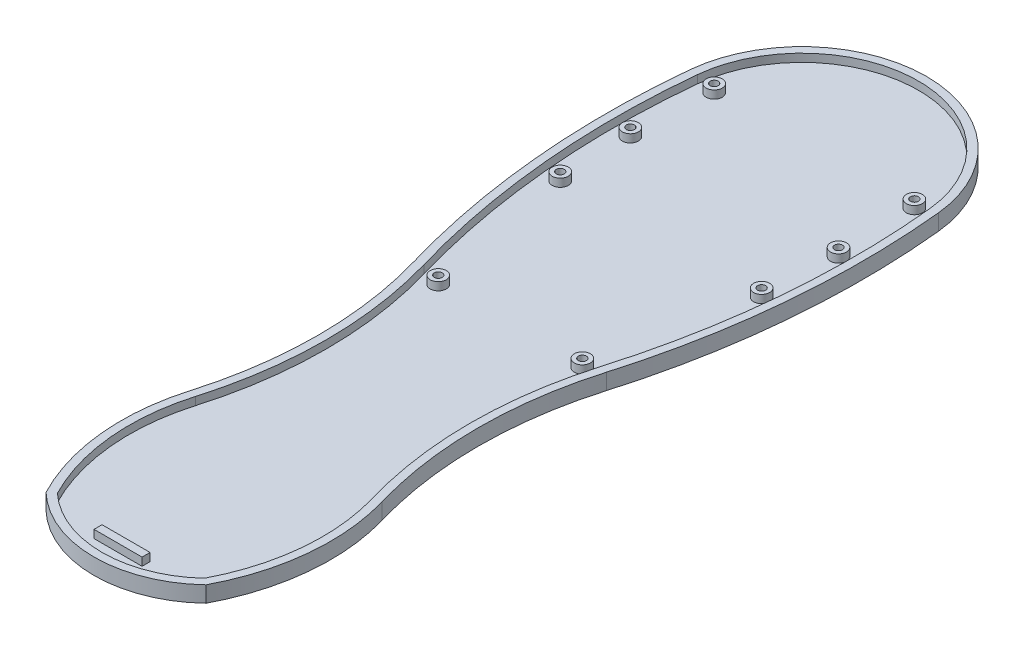
SolidWorks part; units mm, degrees
ref_plane "Front Plane" through (0, 0, 0) normal (0, 0, 1) x (1, 0, 0)
ref_plane "Top Plane" through (0, 0, 0) normal (0, 1, 0) x (1, 0, 0)
ref_plane "Right Plane" through (0, 0, 0) normal (1, 0, 0) x (0, 0, -1)
sketch "Sketch1" plane through (0, 0, 0) normal (0, 1, 0) x (1, 0, 0)
  line L0 (0, 82.55) -> (0, -82.55) construction
  line L1 (-25.4, -82.55) -> (25.4, -82.55)
  line L2 (-25.4, -82.55) -> (-25.4, 82.55)
  line L3 (-25.4, 82.55) -> (25.4, 82.55)
  line L4 (25.4, -82.55) -> (25.4, 82.55)
  line L5 (-25.4, -82.55) -> (25.4, 82.55) construction
  line L6 (-25.4, 82.55) -> (25.4, -82.55) construction
  arc A0 (-24.6082, 60.2854) -> (24.6082, 60.2854) centre (0, 57.8184) cw
  arc A1 (-24.6082, 60.2854) -> (-19.05, 0) centre (133.35, 44.45) ccw
  arc A2 (-19.05, -44.45) -> (-15.875, -76.2) centre (21.8872, -56.39) ccw
  arc A3 (-15.875, -76.2) -> (15.875, -76.2) centre (0, -59.5312) ccw
  arc A4 (-19.05, 0) -> (-19.05, -44.45) centre (-95.25, -22.225) cw
  arc A5 (19.05, -44.45) -> (15.875, -76.2) centre (-21.8872, -56.39) cw
  arc A6 (19.05, 0) -> (19.05, -44.45) centre (95.25, -22.225) ccw
  arc A7 (24.6082, 60.2854) -> (19.05, 0) centre (-133.35, 44.45) cw
  circle A8 centre (0, 44.45) radius 3.175
  point P0 (0, 0)
  point P18 (0, 0)
  point P19 (0, 0)
  point P20 (21.0287, -59.5312)
  point P21 (-19.05, -53.9322)
  point P27 (-15.875, 7.4643)
  point P28 (-19.05, -44.45)
  point P29 (19.05, -44.45)
  point P31 (20.474, 12.5057)
  point P32 (0, 0)
  point P33 (19.05, 8.8523)
  point P40 (0, -82.55)
  dimension "D3" = 38.1
  dimension "D4" = 6.35
  dimension "D1" = 165.1
  dimension "D2" = 50.8
  dimension "D5" = 38.1
  dimension "D6" = 38.1
  dimension "D7" = 6.35
  dimension "D8" = 31.75
  dimension "D9" = 82.55
extrude "Boss-Extrude1" add sketch "Sketch1" along normal blind 3.175 contours A5 A3 A2 A4 A1 A0 A7 A6
sketch "Sketch3" plane through (0, 3.175, 0) normal (0, 1, 0) x (1, 0, 0)
  arc A44 (-17.526, -44.8945) -> (-14.5911, -75.2283) centre (21.8872, -56.39) ccw
  arc A45 (14.5911, -75.2283) -> (17.526, -44.8945) centre (-21.8872, -56.39) ccw
  arc A46 (-14.5911, -75.2283) -> (14.5911, -75.2283) centre (0, -59.5312) ccw
  arc A47 (-17.526, -44.8945) -> (-17.526, 0.4445) centre (-95.25, -22.225) ccw
  arc A48 (17.526, 0.4445) -> (23.0286, 60.1271) centre (-133.35, 44.45) ccw
  arc A49 (17.526, 0.4445) -> (17.526, -44.8945) centre (95.25, -22.225) ccw
  arc A50 (-23.0286, 60.1271) -> (-17.526, 0.4445) centre (133.35, 44.45) ccw
  arc A51 (23.0286, 60.1271) -> (-23.0286, 60.1271) centre (0, 57.8184) ccw
  arc A52 (-17.526, -44.8945) -> (-14.5911, -75.2283) centre (21.8872, -56.39) ccw
  arc A53 (14.5911, -75.2283) -> (17.526, -44.8945) centre (-21.8872, -56.39) ccw
  arc A54 (-14.5911, -75.2283) -> (14.5911, -75.2283) centre (0, -59.5312) ccw
  arc A55 (-17.526, -44.8945) -> (-17.526, 0.4445) centre (-95.25, -22.225) ccw
  arc A56 (17.526, 0.4445) -> (23.0286, 60.1271) centre (-133.35, 44.45) ccw
  arc A57 (17.526, 0.4445) -> (17.526, -44.8945) centre (95.25, -22.225) ccw
  arc A58 (-23.0286, 60.1271) -> (-17.526, 0.4445) centre (133.35, 44.45) ccw
  arc A59 (23.0286, 60.1271) -> (-23.0286, 60.1271) centre (0, 57.8184) ccw
  dimension "D1" = 1.5875
extrude "Cut-Extrude1" cut sketch "Sketch3" against normal blind 1.5875
sketch "Sketch2" plane through (0, 3.175, 0) normal (0, 1, 0) x (1, 0, 0)
  line L0 (0, 0) -> (0, 112.361) construction
  line L1 (-24.6082, 60.2854) -> (24.6082, 60.2854) construction
  line L2 (-25.4, 44.45) -> (25.4, 44.45) construction
  line L3 (-24.7295, 29.8753) -> (24.7295, 29.8753) construction
  line L4 (-19.05, 0) -> (19.05, 0) construction
  line L5 (-20.7557, -56.39) -> (20.7557, -56.39) construction
  line L6 (0, -82.55) -> (0, -56.39) construction
  line L8 (-4.7625, -77.7875) -> (4.7625, -77.7875)
  line L9 (-4.7625, -77.7875) -> (-4.7625, -76.2)
  line L10 (-4.7625, -76.2) -> (4.7625, -76.2)
  line L11 (4.7625, -77.7875) -> (4.7625, -76.2)
  line L12 (-4.7625, -77.7875) -> (4.7625, -76.2) construction
  line L13 (-4.7625, -76.2) -> (4.7625, -77.7875) construction
  arc A0 (-24.6082, 60.2854) -> (-19.05, 0) centre (133.35, 44.45) ccw construction
  arc A1 (19.05, 0) -> (24.6082, 60.2854) centre (-133.35, 44.45) ccw construction
  arc A2 (-19.05, -44.45) -> (-15.875, -76.2) centre (21.8872, -56.39) ccw construction
  arc A3 (15.875, -76.2) -> (19.05, -44.45) centre (-21.8872, -56.39) ccw construction
  circle A4 centre (-19.8457, 60.2854) radius 0.7937
  circle A5 centre (-19.8457, 60.2854) radius 1.5875
  circle A6 centre (-20.6375, 44.45) radius 0.7937
  circle A7 centre (-20.6375, 44.45) radius 1.5875
  circle A8 centre (-19.967, 29.8753) radius 0.7937
  circle A9 centre (-19.967, 29.8753) radius 1.5875
  circle A10 centre (-14.2875, 0) radius 0.7937
  circle A11 centre (-14.2875, 0) radius 1.5875
  arc A12 (-15.875, -76.2) -> (15.875, -76.2) centre (0, -59.5312) ccw construction
  circle A13 centre (19.8457, 60.2854) radius 1.5875
  circle A14 centre (19.8457, 60.2854) radius 0.7937
  circle A15 centre (20.6375, 44.45) radius 0.7937
  circle A16 centre (20.6375, 44.45) radius 1.5875
  circle A17 centre (19.967, 29.8753) radius 0.7937
  circle A18 centre (19.967, 29.8753) radius 1.5875
  circle A19 centre (14.2875, 0) radius 0.7937
  circle A20 centre (14.2875, 0) radius 1.5875
  point P43 (0, -76.9938)
  point P65 (25.4, 44.45)
  dimension "D1" = 1.5875
  dimension "D2" = 3.175
  dimension "D4" = 1.5875
  dimension "D5" = 3.175
  dimension "D6" = 1.5875
  dimension "D7" = 3.175
  dimension "D8" = 1.5875
  dimension "D9" = 3.175
  dimension "D3" = 4.7625
  dimension "D10" = 4.7625
  dimension "D11" = 4.7625
  dimension "D12" = 4.7625
  dimension "D13" = 9.525
  dimension "D14" = 1.5875
  dimension "D15" = 4.7625
  dimension "D16" = 14.5747
  dimension "D17" = 15.8354
extrude "Boss-Extrude3" add sketch "Sketch2" against normal up to surface (1.5875 mm away) up to face at (0, 1.5875, 13.1369)
